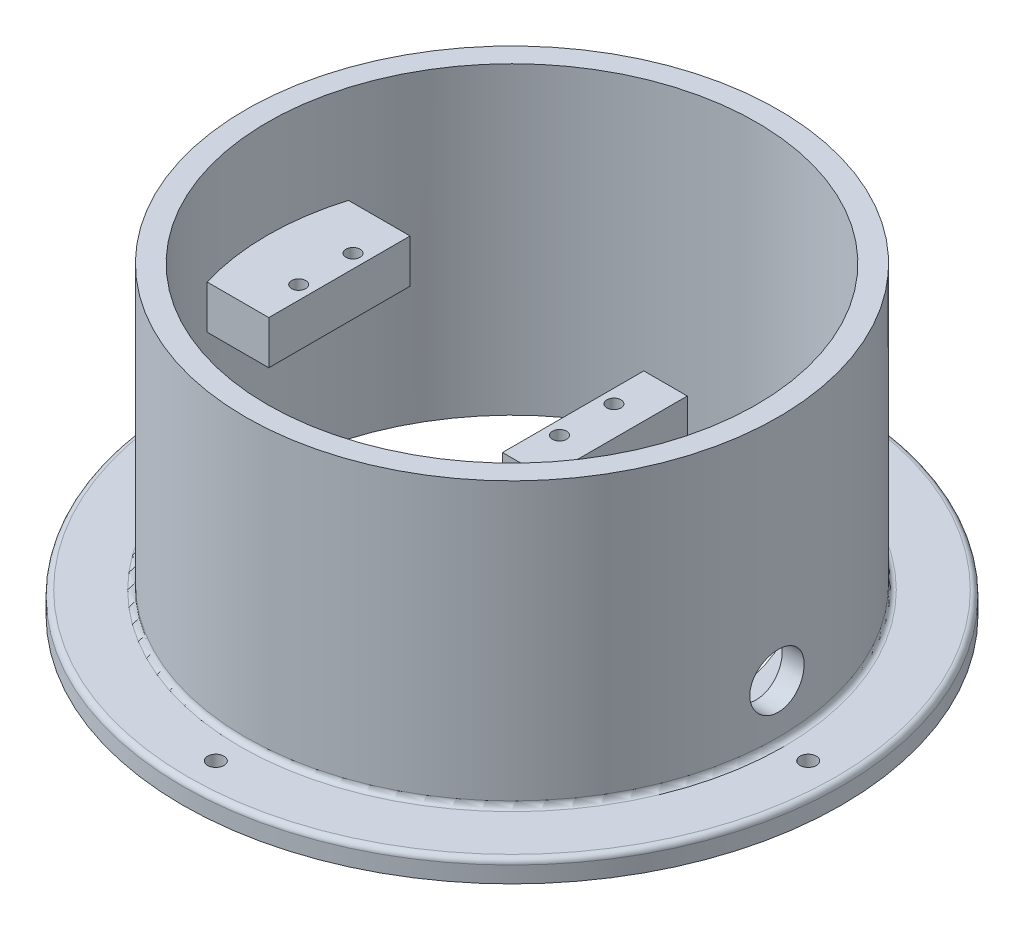
SolidWorks part; units mm, degrees
ref_plane "Front Plane" through (0, 0, 0) normal (0, 0, 1) x (1, 0, 0)
ref_plane "Top Plane" through (0, 0, 0) normal (0, 1, 0) x (1, 0, 0)
ref_plane "Right Plane" through (0, 0, 0) normal (1, 0, 0) x (0, 0, -1)
sketch "Sketch1" plane through (0, 0, 0) normal (0, 1, 0) x (1, 0, 0)
  circle A0 centre (0, 0) radius 60.625
  circle A1 centre (0, 0) radius 45
  dimension "D1" = 121.25
  dimension "D2" = 90
extrude "Boss-Extrude1" add sketch "Sketch1" along normal blind 4
sketch "Sketch2" plane through (0, 4, 0) normal (0, 1, 0) x (1, 0, 0)
  circle A0 centre (0, 0) radius 49
  circle A1 centre (0, 0) radius 45
  dimension "D1" = 90
  dimension "D2" = 98
extrude "Boss-Extrude2" add sketch "Sketch2" along normal blind 52
sketch "Sketch3" plane through (0, 0, 0) normal (0, 0, 1) x (1, 0, 0)
  line L0 (-60.625, 0) -> (60.625, 0) construction
  line L1 (11.25, 0) -> (19.25, 0)
  line L2 (11.25, 0) -> (11.25, 38)
  line L3 (11.25, 38) -> (19.25, 38)
  line L4 (19.25, 0) -> (19.25, 38)
  line L5 (49, 56) -> (-49, 56) construction
  line L6 (-31.75, 38) -> (-46.75, 38)
  line L7 (-31.75, 38) -> (-31.75, 30)
  line L8 (-31.75, 30) -> (-46.75, 30)
  line L9 (-46.75, 38) -> (-46.75, 30)
  dimension "D1" = 8
  dimension "D2" = 38
  dimension "D3" = 11.25
  dimension "D4" = 43
  dimension "D5" = 15
  dimension "D6" = 8
  dimension "D7" = 18
extrude "Boss-Extrude3" add sketch "Sketch3" along normal mid plane 26
sketch "Sketch4" plane through (11.25, 0, 0) normal (-1, 0, 0) x (0, 0, 1)
  line L0 (0, 0) -> (0, 56) construction
  line L1 (49, 56) -> (-49, 56) construction
  line L2 (-60.625, 0) -> (60.625, 0) construction
  line L3 (5, 29) -> (-5, 29)
  line L4 (5, 29) -> (5, 5)
  line L5 (5, 5) -> (-5, 5)
  line L6 (-5, 29) -> (-5, 5)
  line L7 (5, 29) -> (-5, 5) construction
  line L8 (5, 5) -> (-5, 29) construction
  point P5 (0, 17)
  dimension "D1" = 10
  dimension "D2" = 24
  dimension "D3" = 5
extrude "Cut-Extrude1" cut sketch "Sketch4" against normal up to next (8 mm away)
sketch "Sketch5" plane through (11.25, 0, 0) normal (-1, 0, 0) x (0, 0, 1)
  line L0 (-60.625, 0) -> (60.625, 0) construction
  circle A0 centre (0, 14) radius 5
  dimension "D1" = 10
  dimension "D2" = 14
extrude "Cut-Extrude2" cut sketch "Sketch5" against normal through all
sketch "Sketch6" plane through (0, 38, 0) normal (0, 1, 0) x (1, 0, 0)
  line L0 (-49, 0) -> (49, 0) construction
  line L1 (-31.75, -13) -> (-31.75, 13) construction
  line L2 (13.75, 5) -> (-34.25, 5) construction
  line L3 (13.75, 5) -> (13.75, -5) construction
  line L4 (13.75, -5) -> (-34.25, -5) construction
  line L5 (-34.25, 5) -> (-34.25, -5) construction
  line L6 (13.75, 5) -> (-34.25, -5) construction
  line L7 (13.75, -5) -> (-34.25, 5) construction
  line L8 (11.25, -13) -> (11.25, 13) construction
  circle A0 centre (0, 0) radius 49 construction
  circle A1 centre (0, 0) radius 49 construction
  circle A2 centre (-34.25, 5) radius 1.3
  circle A3 centre (-34.25, -5) radius 1.3
  circle A4 centre (13.75, 5) radius 1.3
  circle A5 centre (13.75, -5) radius 1.3
  point P7 (-10.25, 0)
  dimension "D1" = 2.5
  dimension "D2" = 2.5
  dimension "D3" = 10
extrude "Cut-Extrude3" cut sketch "Sketch6" against normal blind 7.2
sketch "Sketch7" plane through (0, 0, 0) normal (0, -1, 0) x (1, 0, 0)
  line L0 (11.25, 13) -> (25.2498, 37.2484)
  line L1 (11.25, 0) -> (19.25, 0) construction
  line L2 (11.25, 13) -> (11.25, -13) construction
  line L3 (11.25, -13) -> (25.2498, -37.2484)
  line L4 (11.25, -13) -> (11.25, 13)
  line L5 (24.25, 19.5167) -> (27.3618, 24.9065)
  line L6 (24.25, -19.5167) -> (27.3618, -24.9065)
  line L7 (19.25, -10.8564) -> (19.25, 10.8564)
  line L8 (24.25, 19.5167) -> (24.25, -19.5167)
  line L9 (19.25, -10.8564) -> (27.3618, -24.9065) construction
  line L10 (24.25, 0) -> (45, 0) construction
  line L11 (19.25, 10.8564) -> (27.3618, 24.9065) construction
  circle A0 centre (0, 0) radius 45 construction
  arc A1 (25.2498, -37.2484) -> (25.2498, 37.2484) centre (0, 0) ccw
  arc A2 (27.3618, -24.9065) -> (27.3618, 24.9065) centre (0, 0) ccw
  line M11 (11.25, -13) -> (19.25, -13)
  line M12 (19.25, -13) -> (19.25, 13)
  line M13 (19.25, 13) -> (11.25, 13)
  dimension "D1" = 60
  dimension "D3" = 5
  dimension "D2" = 8
extrude "Boss-Extrude4" add sketch "Sketch7" against normal blind 4 contours L3 A1 L0 A2 L6 L8 L5 M13 M12 M11
sketch "Sketch8" plane through (0, 0, 0) normal (0, -1, 0) x (1, 0, 0)
  circle A0 centre (0, 0) radius 54.5 construction
  circle A1 centre (54.5, 0) radius 1.5
  circle A2 centre (0, 0) radius 54.5 construction
  circle A3 centre (0, -54.5) radius 1.5
  circle A4 centre (0, 0) radius 54.5 construction
  circle A5 centre (-54.5, 0) radius 1.5
  circle A6 centre (0, 0) radius 54.5 construction
  circle A7 centre (0, 54.5) radius 1.5
  point P17 (0, 0)
  dimension "D1" = 109
  dimension "D2" = 3
  dimension "D3" = 4
extrude "Cut-Extrude4" cut sketch "Sketch8" against normal through all
fillet "Fillet1" radius 1 2 edges at (0, 4, 60.625) (0, 4, 49)
